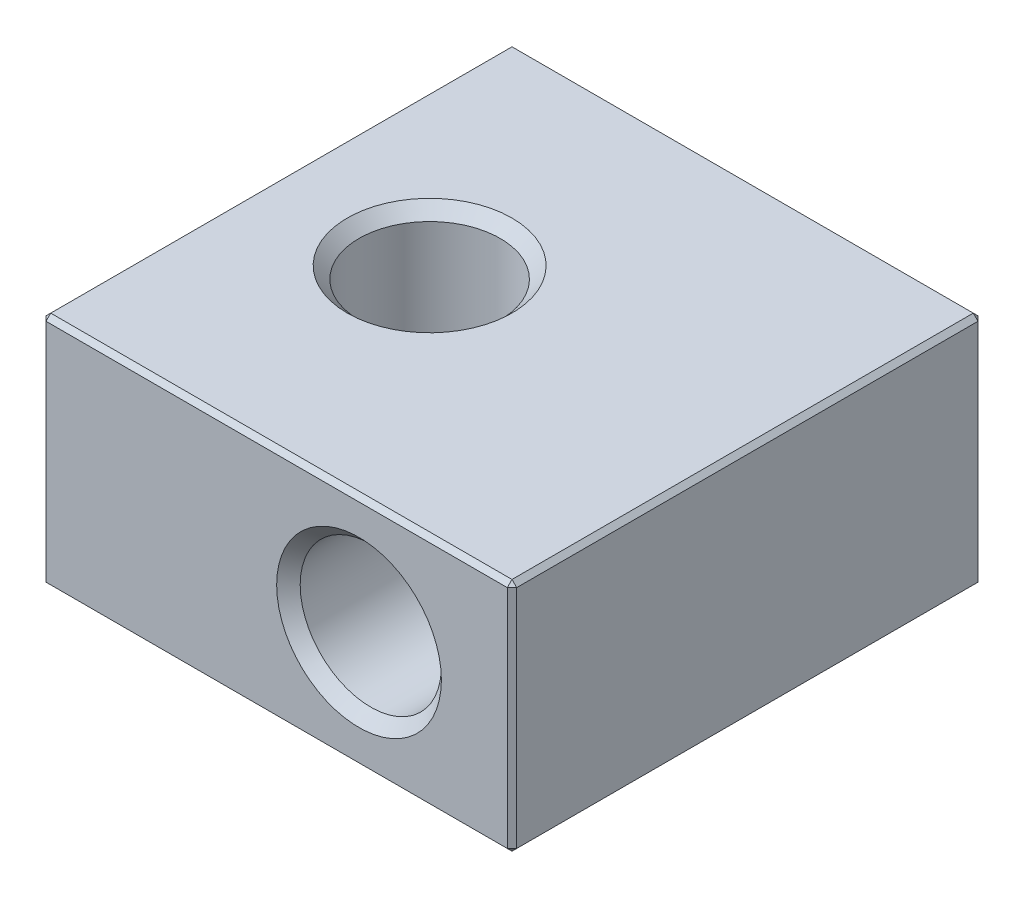
SolidWorks part; units mm, degrees
ref_plane "前视基准面" through (0, 0, 0) normal (0, 0, 1) x (1, 0, 0)
ref_plane "上视基准面" through (0, 0, 0) normal (0, 1, 0) x (1, 0, 0)
ref_plane "右视基准面" through (0, 0, 0) normal (1, 0, 0) x (0, 0, -1)
sketch "草图1" plane through (0, 0, 0) normal (0, 1, 0) x (1, 0, 0)
  line L0 (-1.068, -3.1553) -> (18.932, -3.1553) construction
  line L1 (-1.068, 6.8447) -> (18.932, 6.8447)
  line L2 (-1.068, 6.8447) -> (-1.068, -13.1553)
  line L3 (-1.068, -13.1553) -> (18.932, -13.1553)
  line L4 (18.932, 6.8447) -> (18.932, -13.1553)
  line L5 (-1.068, 6.8447) -> (18.932, -13.1553) construction
  line L6 (-1.068, -13.1553) -> (18.932, 6.8447) construction
  circle A0 centre (5.432, -3.1553) radius 3
  point P4 (8.932, -3.1553)
  dimension "D3" = 6
  dimension "D1" = 20
  dimension "D2" = 20
  dimension "D4" = 6.5
extrude "凸台-拉伸1" add sketch "草图1" along normal blind 10
sketch "草图2" plane through (0, 0, -6.8447) normal (0, 0, -1) x (-1, 0, 0)
  line L0 (-18.932, 5) -> (1.068, 5) construction
  line L1 (-18.932, 10) -> (-18.932, 0) construction
  line L2 (1.068, 10) -> (1.068, 0) construction
  circle A0 centre (-12.432, 5) radius 3
  dimension "D1" = 6
  dimension "D2" = 13.5
extrude "切除-拉伸1" cut sketch "草图2" against normal through all
chamfer "倒角3" distance 0.5 angle 45 4 edges at (9.432, 5, -6.8447) (5.432, 10, 6.1553) (5.432, 0, 6.1553) (9.432, 5, 13.1553)
chamfer "倒角4" distance 0.2 angle 45 12 edges at (18.932, 10, 3.1553) (8.932, 0, 13.1553) (18.932, 5, 13.1553) (18.932, 0, 3.1553) (18.932, 5, -6.8447) (8.932, 10, -6.8447) (-1.068, 5, -6.8447) (8.932, 0, -6.8447) (-1.068, 0, 3.1553) (-1.068, 10, 3.1553) (8.932, 10, 13.1553) (-1.068, 5, 13.1553)
